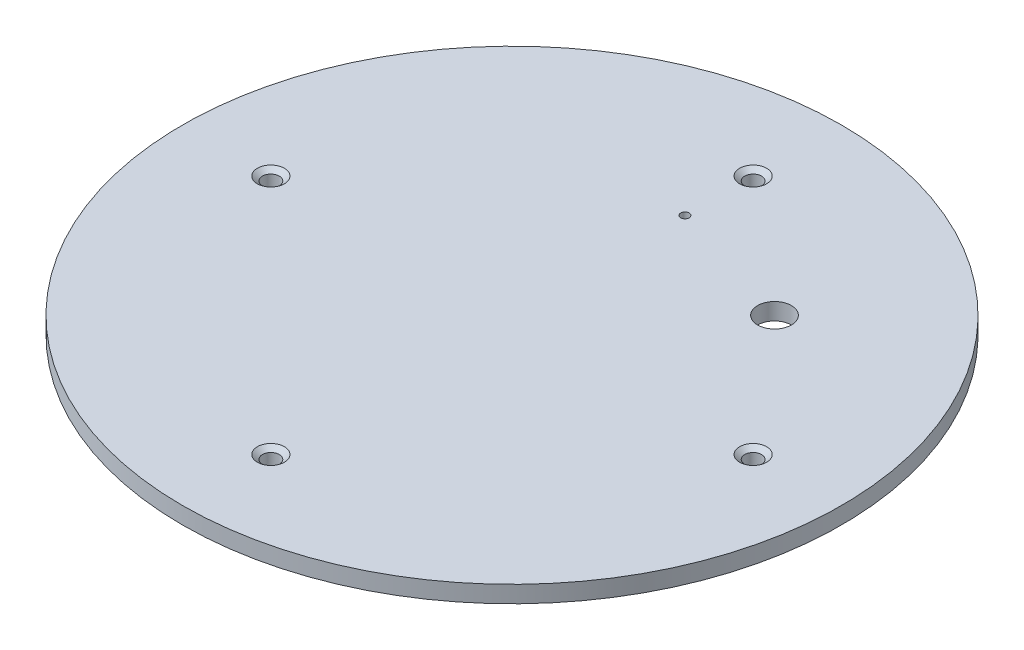
SolidWorks part; units mm, degrees
material "1060 Alloy"
ref_plane "Front Plane" through (0, 0, 0) normal (0, 0, 1) x (1, 0, 0)
ref_plane "Top Plane" through (0, 0, 0) normal (0, 1, 0) x (1, 0, 0)
ref_plane "Right Plane" through (0, 0, 0) normal (1, 0, 0) x (0, 0, -1)
sketch "Sketch1" plane through (0, 0, 0) normal (0, 1, 0) x (1, 0, 0)
  circle A0 centre (0, 0) radius 19.53
  dimension "D1" = 39.06
extrude "Boss-Extrude1" add sketch "Sketch1" along normal blind 1
sketch "Sketch6" plane through (0, 1, 0) normal (0, 1, 0) x (1, 0, 0)
  line L0 (0, 0) -> (13.1331, 13.1331) construction
  line L1 (0, 0) -> (0, 10.25) construction
  circle A0 centre (0, 10.25) radius 0.25
  circle A1 centre (7.7782, 7.7782) radius 1
  dimension "D1" = 10.25
  dimension "D3" = 0.5
  dimension "D4" = 2
  dimension "D2" = 0
  dimension "D5" = 11
  dimension "D6" = 45
extrude "Cut-Extrude1" cut sketch "Sketch6" against normal through all both and the other way through all
hole_wizard "CSK for M2 Flat Head Machine Screw1" positions "Sketch13" profile "Sketch14" countersink size "M2" standard "ANSI Metric" end condition through all
sketch "Sketch13" plane through (0, 1, 0) normal (0, 1, 0) x (1, 0, 0)
  point P0 (0, 14.29)
  point P2 (-14.29, 0)
  point P4 (0, -14.29)
  point P6 (14.29, 0)
  dimension "D1" = 14.29
  dimension "D2" = 14.29
  dimension "D3" = 14.29
  dimension "D4" = 14.29
sketch "Sketch14" plane through (0, 1, -14.29) normal (1, 0, 0) x (0, 0, 1)
  line L0 (0, 0) -> (0, 1)
  line L1 (0, 1) -> (0.5, 1)
  line L2 (0.5, 1) -> (0.5, 0.2517)
  line L3 (0.5, 0.2517) -> (0.8, 0)
  line L5 (0.8, 0) -> (0, 0)
  line L6 (-0.5, 0.2517) -> (-0.8, 0) construction
  line L11 (0, -6.35) -> (0, 107.95) construction
  dimension "Thru Hole Dia." = 1
  dimension "Thru Hole Depth" = 1
  dimension "Near C'Sink Dia." = 1.6
  dimension "Near C'Sink Angle" = 100
